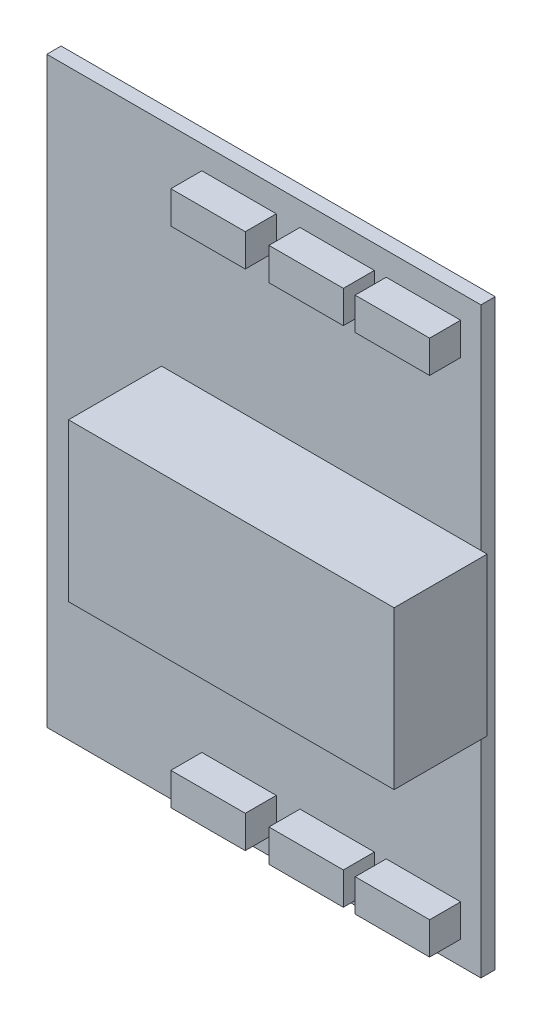
SolidWorks part; units mm, degrees
ref_plane "Ground" through (0, 0, 0) normal (0, 0, 1) x (1, 0, 0)
ref_plane "Right" through (0, 0, 0) normal (0, 1, 0) x (1, 0, 0)
ref_plane "Front" through (0, 0, 0) normal (1, 0, 0) x (0, 0, -1)
sketch "Sketch2" plane through (0, 0, 0) normal (0, 0, 1) x (1, 0, 0)
  line L1 (-35, -47) -> (35, -47)
  line L2 (-35, -47) -> (-35, 47)
  line L3 (-35, 47) -> (35, 47)
  line L4 (35, -47) -> (35, 47)
  line L5 (-35, -47) -> (35, 47) construction
  line L6 (-35, 47) -> (35, -47) construction
  point P0 (0, 0)
  dimension "D1" = 70
  dimension "D2" = 94
extrude "Boss-Extrude1" add sketch "Sketch2" along normal blind 2.3
sketch "Sketch3" plane through (0, 0, 2.3) normal (0, 0, 1) x (1, 0, 0)
  line L0 (-35, 0) -> (35, 0) construction
  line L1 (35, 12.7) -> (-16.5, 12.7)
  line L2 (35, 12.7) -> (35, -12.7)
  line L3 (-16.5, 12.7) -> (-16.5, -12.7)
  line L4 (35, -47) -> (35, 47)
  line L5 (35, 47) -> (-35, 47)
  line L6 (-35, 47) -> (-35, -47)
  line L7 (-35, -47) -> (35, -47)
  line L8 (35, -47) -> (35, 47)
  line L9 (35, 47) -> (-35, 47)
  line L10 (-35, 47) -> (-35, -47)
  line L11 (-35, -47) -> (35, -47)
  line L12 (35, -12.7) -> (-16.5, -12.7)
  line L13 (35, -12.7) -> (35, 12.7)
  line L14 (35, 12.7) -> (36, 12.7)
  line L15 (36, 12.7) -> (36, -12.7)
  line L16 (36, -12.7) -> (35, -12.7)
  point P6 (-16.5, 0)
  line M10 (35, -47) -> (35, 47)
  dimension "D2" = 51.5
  dimension "D3" = 25.4
  dimension "D4" = 1
  dimension "D1" = 0
extrude "Boss-Extrude2" add sketch "Sketch3" along normal blind 15 contours L3 L0 L8 L1 | L0 L3 L12 M10 | L16 L15 L14 L13 M10
sketch "Sketch4" plane through (0, 0, 2.3) normal (0, 0, 1) x (1, 0, 0)
  line L0 (-10, 38) -> (29, 38) construction
  line L1 (-35, 0) -> (35, 0) construction
  line L2 (-10, 38) -> (2, 38)
  line L3 (-10, 38) -> (-10, 43.2205)
  line L4 (-10, 43.2205) -> (2, 43.2205)
  line L5 (2, 38) -> (2, 43.2205)
  line L6 (5.8182, 38) -> (17.8182, 38)
  line L7 (5.8182, 38) -> (5.8182, 43.2205)
  line L8 (-16.5, 12.7) -> (35, 12.7)
  line L9 (35, 12.7) -> (35, 47)
  line L10 (35, 47) -> (-35, 47)
  line L11 (-35, 47) -> (-35, -47)
  line L12 (-35, -47) -> (35, -47)
  line L13 (35, -47) -> (35, -12.7)
  line L14 (35, -12.7) -> (-16.5, -12.7)
  line L15 (-16.5, -12.7) -> (-16.5, 12.7)
  line L16 (-16.5, 12.7) -> (35, 12.7)
  line L17 (35, 12.7) -> (35, 47)
  line L18 (35, 47) -> (-35, 47)
  line L19 (-35, 47) -> (-35, -47)
  line L20 (-35, -47) -> (35, -47)
  line L21 (35, -47) -> (35, -12.7)
  line L22 (35, -12.7) -> (-16.5, -12.7)
  line L23 (-16.5, -12.7) -> (-16.5, 12.7)
  line L24 (5.8182, 43.2205) -> (17.8182, 43.2205)
  line L25 (17.8182, 38) -> (17.8182, 43.2205)
  line L26 (19.7253, 38) -> (31.7253, 38)
  line L27 (19.7253, 38) -> (19.7253, 43.2205)
  line L28 (19.7253, 43.2205) -> (31.7253, 43.2205)
  line L29 (31.7253, 38) -> (31.7253, 43.2205)
  line L31 (19.7253, -43.2205) -> (31.7253, -43.2205)
  line L32 (31.7253, -38) -> (31.7253, -43.2205)
  line L33 (19.7253, -38) -> (31.7253, -38)
  line L34 (19.7253, -38) -> (19.7253, -43.2205)
  line L35 (5.8182, -43.2205) -> (17.8182, -43.2205)
  line L36 (17.8182, -38) -> (17.8182, -43.2205)
  line L37 (5.8182, -38) -> (17.8182, -38)
  line L38 (5.8182, -38) -> (5.8182, -43.2205)
  line L39 (-10, -43.2205) -> (2, -43.2205)
  line L40 (2, -38) -> (2, -43.2205)
  line L41 (-10, -38) -> (2, -38)
  line L42 (-10, -38) -> (-10, -43.2205)
  dimension "D2" = 39
  dimension "D3" = 6
  dimension "D4" = 12
  dimension "D5" = 9
  dimension "D1" = 0
extrude "Boss-Extrude3" add sketch "Sketch4" along normal blind 5 contours L2 L5 L4 L3 | L6 L25 L24 L7 | L26 L29 L28 L27 | L41 L42 L39 L40 | L37 L38 L35 L36 | L33 L34 L31 L32
